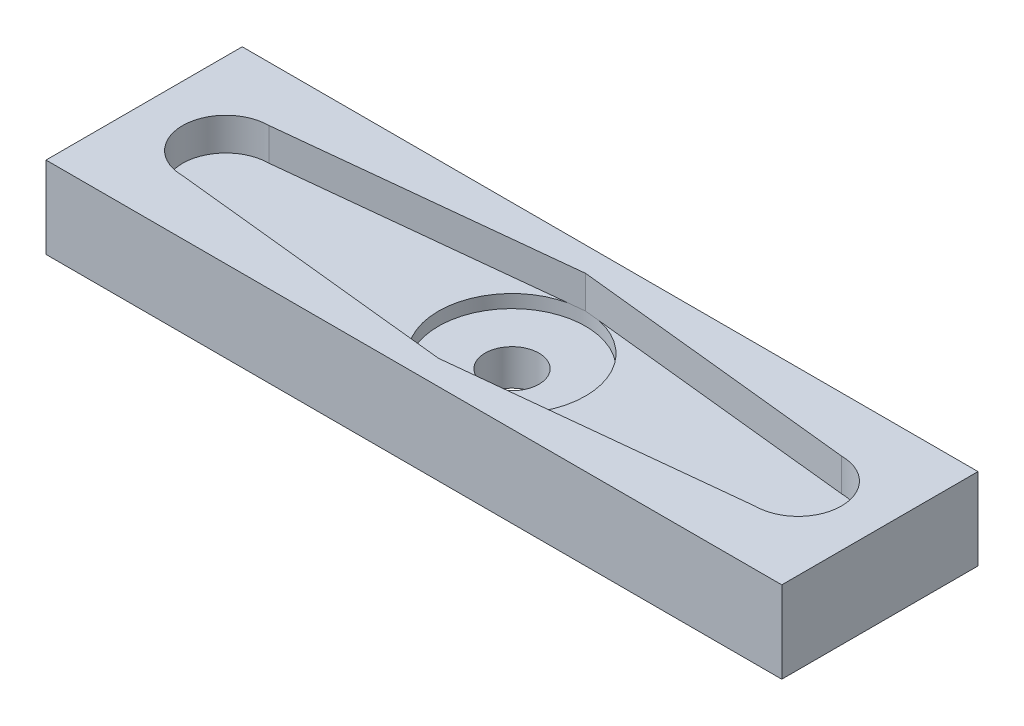
SolidWorks part; units mm, degrees
ref_plane "Front Plane" through (0, 0, 0) normal (0, 0, 1) x (1, 0, 0)
ref_plane "Top Plane" through (0, 0, 0) normal (0, 1, 0) x (1, 0, 0)
ref_plane "Right Plane" through (0, 0, 0) normal (1, 0, 0) x (0, 0, -1)
sketch "Sketch1" plane through (0, 0, 0) normal (0, 1, 0) x (1, 0, 0)
  line L1 (-22.5, 6) -> (22.5, 6)
  line L2 (-22.5, 6) -> (-22.5, -6)
  line L3 (-22.5, -6) -> (22.5, -6)
  line L4 (22.5, 6) -> (22.5, -6)
  line L5 (-22.5, 6) -> (22.5, -6) construction
  line L6 (-22.5, -6) -> (22.5, 6) construction
  point P0 (0, 0)
  dimension "D1" = 45
  dimension "D2" = 12
extrude "Boss-Extrude1" add sketch "Sketch1" along normal blind 5
sketch "Sketch2" plane through (0, 5, 0) normal (0, 1, 0) x (1, 0, 0)
  line L0 (-17.5, 2.65) -> (0, 4.5)
  line L1 (0, 4.5) -> (17.5, 2.65)
  line L2 (-17.5, -2.65) -> (0, -4.5)
  line L3 (0, -4.5) -> (17.5, -2.65)
  circle A0 centre (0, 0) radius 4.5
  circle A1 centre (17.5, 0) radius 2.65
  circle A2 centre (-17.5, 0) radius 2.65
  dimension "D1" = 9
  dimension "D2" = 5.3
  dimension "D3" = 5.3
  dimension "D4" = 17.5
  dimension "D5" = 17.5
extrude "Cut-Extrude1" cut sketch "Sketch2" against normal blind 2 contours A2 | A2 L2 A0 L0 | L3 A0 L1 L0 L2 | A1 L1 A0 L3 | A1
sketch "Sketch3" plane through (0, 3, 0) normal (0, 1, 0) x (1, 0, 0)
  circle A0 centre (0, 0) radius 1.65
  dimension "D1" = 3.3
extrude "Cut-Extrude2" cut sketch "Sketch3" against normal blind 12
sketch "Sketch4" plane through (0, 3, 0) normal (0, 1, 0) x (1, 0, 0)
  circle A0 centre (0, 0) radius 4.5
  point P4 (0, 0)
extrude "Cut-Extrude3" cut sketch "Sketch4" against normal blind 0.8
